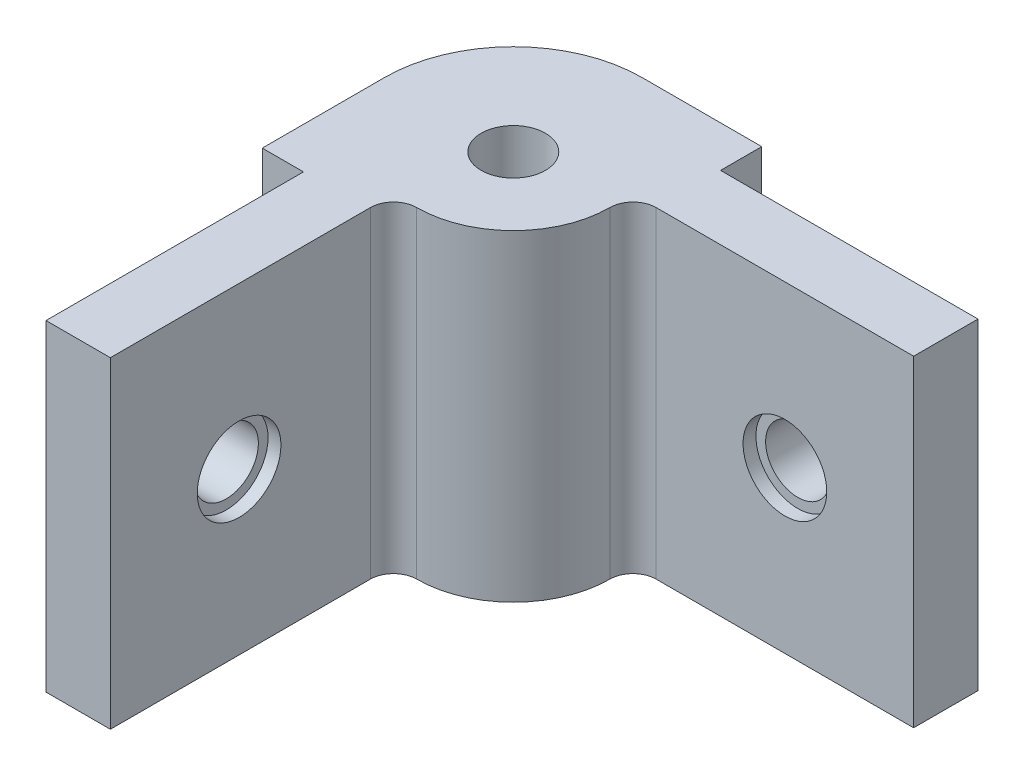
SolidWorks part; units mm, degrees
material "ABS"
ref_plane "Front Plane" through (0, 0, 0) normal (0, 0, 1) x (1, 0, 0)
ref_plane "Top Plane" through (0, 0, 0) normal (0, 1, 0) x (1, 0, 0)
ref_plane "Right Plane" through (0, 0, 0) normal (1, 0, 0) x (0, 0, -1)
sketch "Sketch4" plane through (0, 0, 0) normal (0, 1, 0) x (1, 0, 0)
  line L12 (12.8597, 14.3012) -> (32.8597, 14.3012)
  line L18 (3.5597, 22.5012) -> (3.5597, 12.5012) construction
  line L19 (12.8597, 12.5012) -> (11.0597, 12.5012) construction
  line L20 (-6.4403, 12.5012) -> (-6.4403, 3.0012)
  line L27 (12.8597, 14.3012) -> (12.8597, 12.5012) construction
  line L28 (3.5597, 5.0012) -> (3.5597, 3.2012) construction
  line L29 (3.5597, 3.2012) -> (1.7597, 3.2012) construction
  line L35 (1.7597, 3.2012) -> (1.7597, -16.9988)
  line L40 (3.5597, 12.5012) -> (-6.4403, 12.5012) construction
  line L42 (11.0597, 12.5012) -> (3.5597, 12.5012) construction
  line L44 (-6.4403, 3.0012) -> (-3.2403, 3.0012)
  line L45 (-3.2403, 3.0012) -> (-3.2403, -16.9988)
  line L46 (-3.2403, -16.9988) -> (1.7597, -16.9988)
  line L47 (3.5597, 12.5012) -> (3.5597, 5.0012) construction
  line L50 (3.5597, 22.5012) -> (12.8597, 22.5012)
  line L51 (12.8597, 22.5012) -> (12.8597, 19.3012)
  line L52 (12.8597, 19.3012) -> (32.8597, 19.3012)
  line L53 (32.8597, 19.3012) -> (32.8597, 14.3012)
  line L55 (5.3274, 10.7334) -> (8.863, 7.1979) construction
  line L56 (5.3274, 10.7334) -> (3.5597, 12.5012) construction
  arc A2 (3.5597, 22.5012) -> (-6.4403, 12.5012) centre (3.5597, 12.5012) ccw
  arc A6 (3.5597, 5.0012) -> (1.7597, 3.2012) centre (3.5597, 3.2012) ccw
  arc A7 (11.0597, 12.5012) -> (12.8597, 14.3012) centre (12.8597, 12.5012) cw
  circle A14 centre (3.5597, 12.5012) radius 2.5
  arc A17 (11.0597, 12.5012) -> (3.5597, 5.0012) centre (3.5597, 12.5012) cw
extrude "Boss-Extrude1" add sketch "Sketch4" along normal blind 25
sketch "Sketch5" plane through (0, 0, -19.3012) normal (0, 0, -1) x (-1, 0, 0)
  line L0 (-12.8597, 25) -> (-32.8597, 25) construction
  line L1 (-22.8597, 25) -> (-22.8597, 0) construction
  line L2 (-32.8597, 0) -> (-12.8597, 0) construction
  circle A0 centre (-22.8597, 12.5) radius 2.5
  point P2 (-22.8597, 25)
  point P9 (-22.8597, 12.5)
  dimension "D1" = 5
extrude "Cut-Extrude1" cut sketch "Sketch5" against normal through all
sketch "Sketch6" plane through (0, 0, -14.3012) normal (0, 0, 1) x (1, 0, 0)
  circle A0 centre (22.8597, 12.5) radius 3.25
  circle A1 centre (22.8597, 12.5) radius 2.5 construction
  dimension "D1" = 6.5
extrude "Cut-Extrude2" cut sketch "Sketch6" against normal blind 1
sketch "Sketch7" plane through (1.7597, 0, 0) normal (1, 0, 0) x (0, 0, -1)
  line L0 (-16.9988, 25) -> (3.0012, 25) construction
  line L1 (-6.9988, 25) -> (-6.9988, 0) construction
  line L2 (3.0012, 0) -> (-16.9988, 0) construction
  circle A0 centre (-6.9988, 12.5) radius 2.5
  point P2 (-6.9988, 25)
  point P9 (-6.9988, 12.5)
  dimension "D1" = 5
extrude "Cut-Extrude3" cut sketch "Sketch7" against normal through all
sketch "Sketch8" plane through (1.7597, 0, 0) normal (1, 0, 0) x (0, 0, -1)
  circle A0 centre (-6.9988, 12.5) radius 3.25
  dimension "D1" = 6.5
extrude "Cut-Extrude4" cut sketch "Sketch8" against normal blind 1
equation "\"tolerance\"= 0.1mm"
